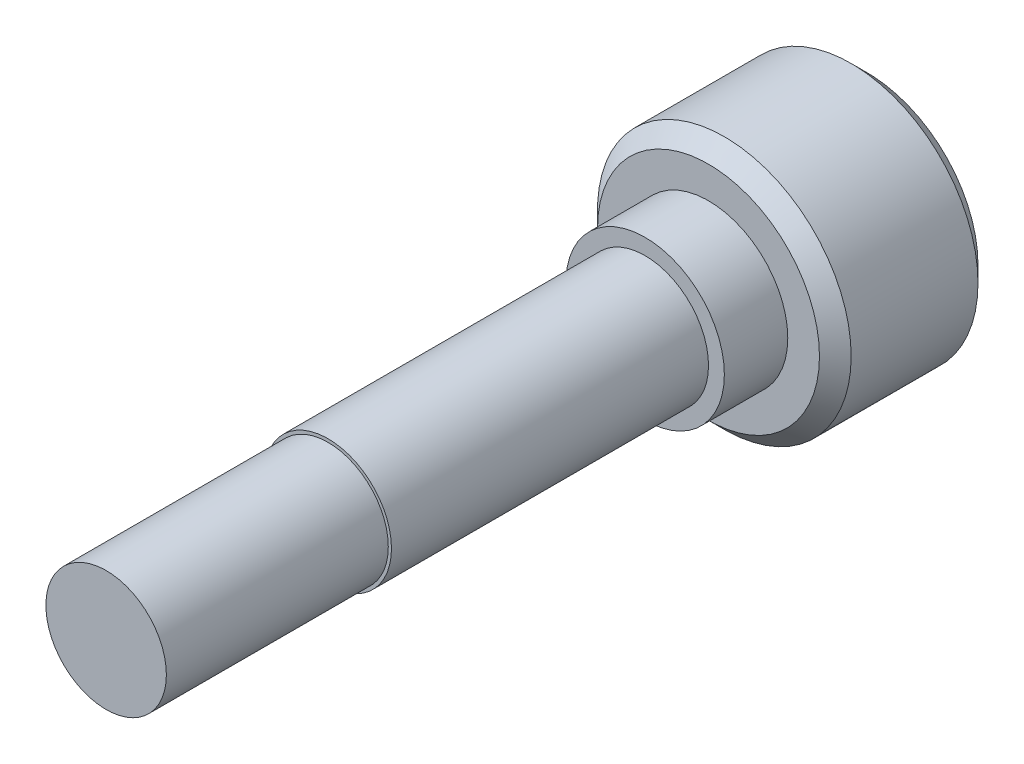
SolidWorks part; units mm, degrees
ref_plane "前视基准面" through (0, 0, 0) normal (0, 0, 1) x (1, 0, 0)
ref_plane "上视基准面" through (0, 0, 0) normal (0, 1, 0) x (1, 0, 0)
ref_plane "右视基准面" through (0, 0, 0) normal (1, 0, 0) x (0, 0, -1)
sketch "草图1" plane through (0, 0, 0) normal (0, 0, 1) x (1, 0, 0)
  circle A0 centre (0, 0) radius 4
  dimension "D1" = 8
extrude "凸台-拉伸1" add sketch "草图1" along normal blind 5
sketch "草图2" plane through (0, 0, 5) normal (0, 0, 1) x (1, 0, 0)
  circle A0 centre (0, 0) radius 2.5
  dimension "D1" = 5
extrude "凸台-拉伸2" add sketch "草图2" along normal blind 2
sketch "草图3" plane through (0, 0, 7) normal (0, 0, 1) x (1, 0, 0)
  circle A0 centre (0, 0) radius 2
  dimension "D1" = 4
extrude "凸台-拉伸3" add sketch "草图3" along normal blind 17
chamfer "倒角1" distance 0.5 angle 45 1 edges at (4, 0, 0)
chamfer "倒角2" distance 0.5 angle 45 1 edges at (4, 0, 5)
sketch "草图4" plane through (0, 0, 24) normal (0, 0, 1) x (1, 0, 0)
  circle A0 centre (0, 0) radius 2
  circle A1 centre (0, 0) radius 1.9
  dimension "D1" = 4
  dimension "D2" = 3.8
extrude "切除-拉伸1" cut sketch "草图4" against normal blind 7
